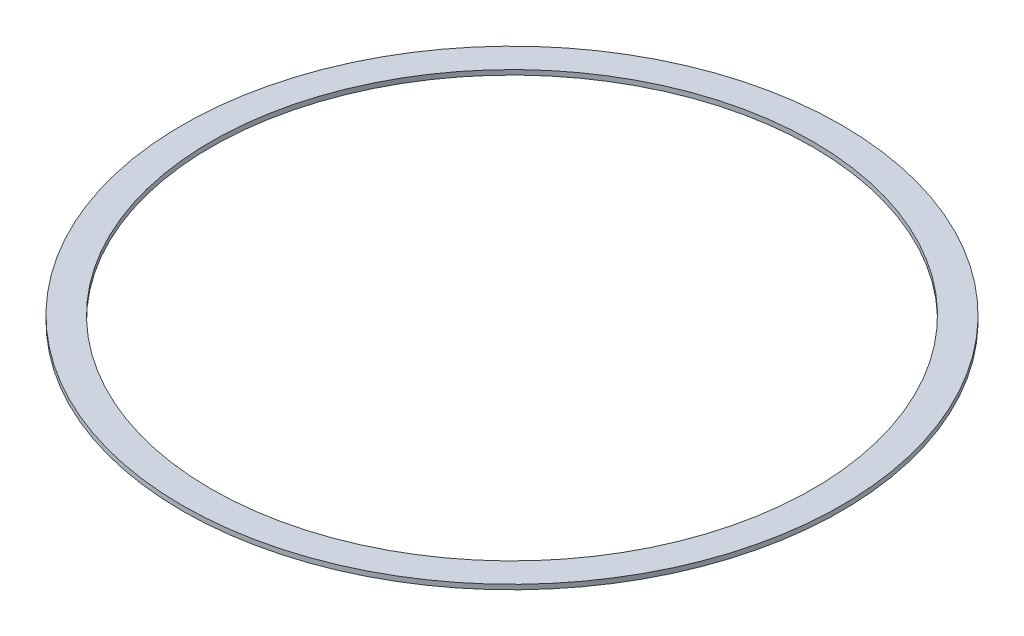
SolidWorks part; units mm, degrees
ref_plane "Front Plane" through (0, 0, 0) normal (0, 0, 1) x (1, 0, 0)
ref_plane "Top Plane" through (0, 0, 0) normal (0, 1, 0) x (1, 0, 0)
ref_plane "Right Plane" through (0, 0, 0) normal (1, 0, 0) x (0, 0, -1)
sketch "Sketch1" plane through (0, 0, 0) normal (0, 1, 0) x (1, 0, 0)
  circle A0 centre (-843.7032, -2673.069) radius 175.26
  circle A1 centre (-843.7032, -2673.069) radius 160.02
  circle A3 centre (-843.7032, -2673.069) radius 175.26 construction
  circle A4 centre (-843.7032, -2673.069) radius 160.02 construction
extrude "Boss-Extrude1" add sketch "Sketch1" along normal blind 2.54
